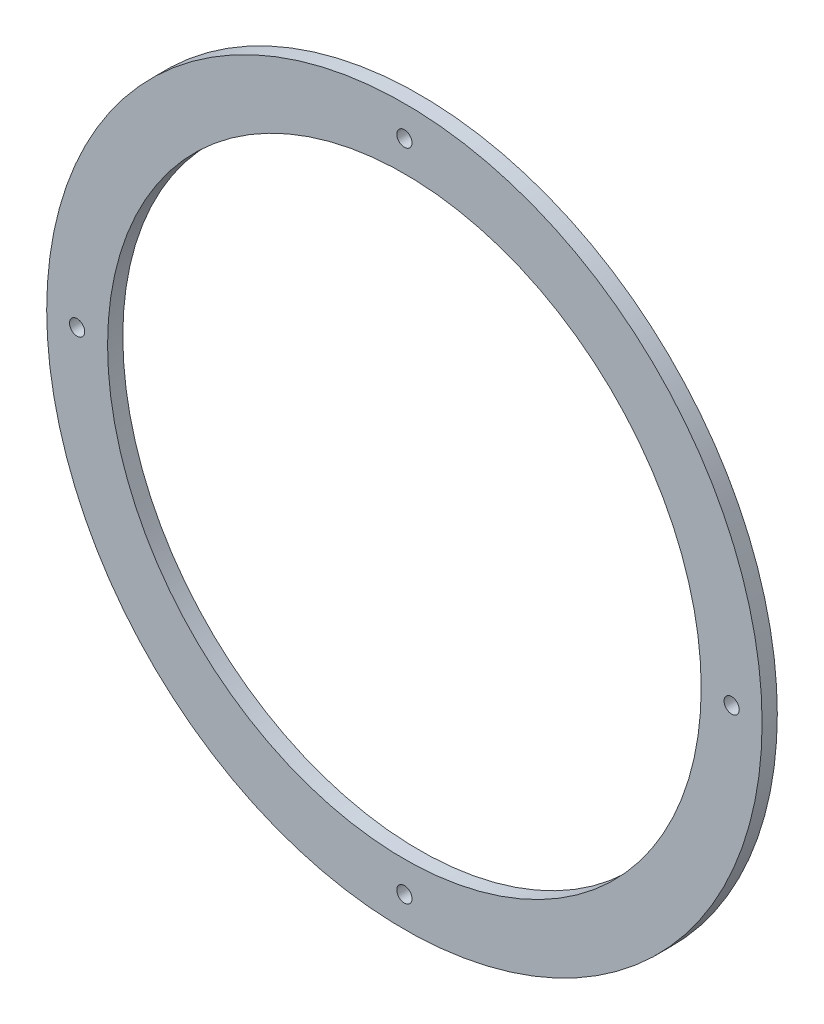
SolidWorks part; units mm, degrees
ref_plane "Front Plane" through (0, 0, 0) normal (0, 0, 1) x (1, 0, 0)
ref_plane "Top Plane" through (0, 0, 0) normal (0, 1, 0) x (1, 0, 0)
ref_plane "Right Plane" through (0, 0, 0) normal (1, 0, 0) x (0, 0, -1)
sketch "Sketch1" plane through (0, 0, 0) normal (0, 0, 1) x (1, 0, 0)
  circle A0 centre (0, 0) radius 149.225
  circle A1 centre (0, 0) radius 123.825
  circle A2 centre (0, 136.525) radius 3.175
  circle A3 centre (136.525, 0) radius 3.175
  circle A4 centre (0, -136.525) radius 3.175
  circle A5 centre (-136.525, 0) radius 3.175
  point P15 (0, 0)
  dimension "D2" = 6.35
  dimension "D4" = 298.45
  dimension "D5" = 247.65
  dimension "D3" = 136.525
  dimension "D1" = 4
extrude "Boss-Extrude1" add sketch "Sketch1" along normal blind 6.35
